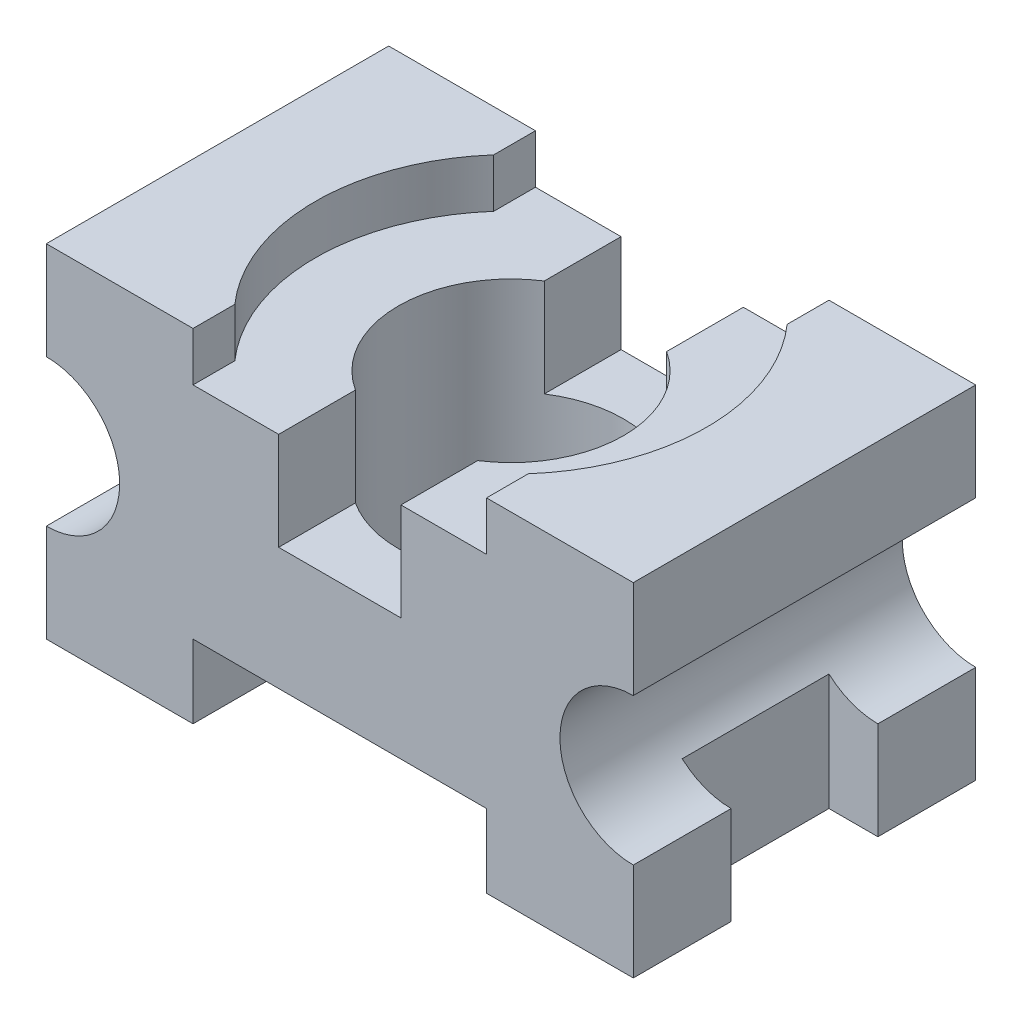
SolidWorks part; units mm, degrees
ref_plane "Front Plane" through (0, 0, 0) normal (0, 0, 1) x (1, 0, 0)
ref_plane "Top Plane" through (0, 0, 0) normal (0, 1, 0) x (1, 0, 0)
ref_plane "Right Plane" through (0, 0, 0) normal (1, 0, 0) x (0, 0, -1)
sketch "Sketch1" plane through (0, 0, 0) normal (0, 0, 1) x (1, 0, 0)
  line L0 (-60.0631, -25.7154) -> (-60.0631, -45.7154)
  line L1 (-60.0631, -45.7154) -> (-30.0631, -45.7154)
  line L2 (-0.0631, -45.7154) -> (-0.0631, 24.2846) construction
  line L3 (-60.0631, 4.2846) -> (-60.0631, 24.2846)
  line L4 (-60.0631, 24.2846) -> (-30.0631, 24.2846)
  line L5 (-30.0631, 24.2846) -> (-30.0631, 14.2846)
  line L6 (-30.0631, 14.2846) -> (-12.5631, 14.2846)
  line L7 (-12.5631, 14.2846) -> (-12.5631, -5.7154)
  line L8 (-12.5631, -5.7154) -> (12.4369, -5.7154)
  line L9 (12.4369, 14.2846) -> (12.4369, -5.7154)
  line L10 (-30.0631, -45.7154) -> (-30.0631, -30.7154)
  line L11 (-30.0631, -30.7154) -> (29.9369, -30.7154)
  line L12 (29.9369, 14.2846) -> (12.4369, 14.2846)
  line L13 (29.9369, 24.2846) -> (29.9369, 14.2846)
  line L14 (59.9369, 24.2846) -> (29.9369, 24.2846)
  line L15 (59.9369, 4.2846) -> (59.9369, 24.2846)
  line L16 (59.9369, -25.7154) -> (59.9369, -45.7154)
  line L17 (59.9369, -45.7154) -> (29.9369, -45.7154)
  line L18 (29.9369, -45.7154) -> (29.9369, -30.7154)
  arc A0 (-60.0631, -25.7154) -> (-60.0631, 4.2846) centre (-60.0631, -10.7154) ccw
  arc A1 (59.9369, -25.7154) -> (59.9369, 4.2846) centre (59.9369, -10.7154) cw
  point P16 (-0.0631, -5.7154)
  point P26 (-0.0631, -30.7154)
extrude "Boss-Extrude1" add sketch "Sketch1" along normal blind 70
sketch "Sketch2" plane through (0, 24.2846, 0) normal (0, 1, 0) x (1, 0, 0)
  circle A0 centre (-0.0631, -35) radius 40
extrude "Cut-Extrude1" cut sketch "Sketch2" against normal blind 10
sketch "Sketch3" plane through (0, 14.2846, 0) normal (0, 1, 0) x (1, 0, 0)
  circle A0 centre (-0.0631, -35) radius 23
extrude "Cut-Extrude2" cut sketch "Sketch3" against normal blind 66
sketch "Sketch4" plane through (-60.0631, 0, 0) normal (-1, 0, 0) x (0, 0, 1)
  line L0 (70, -45.7154) -> (50, -45.7154)
  line L1 (70, -45.7154) -> (0, -45.7154) construction
  line L2 (50, -45.7154) -> (20, -45.7154)
  line L3 (20, -45.7154) -> (20, -10.7154)
  line L5 (20, -10.7154) -> (50, -10.7154)
  line L6 (50, -10.7154) -> (50, -45.7154)
  line M2 (0, -45.7154) -> (70, -45.7154)
  line M4 (70, -25.7154) -> (0, -25.7154)
extrude "Cut-Extrude3" cut sketch "Sketch4" against normal blind 10 contours L6 L5 L3 M4 | L6 L3 M4 M2
ref_plane "Plane1" through (-0.0631, 0, 0) normal (-1, 0, 0) x (0, 0, 1)
mirror "Mirror1" about plane through (-0.0631, 0, 0) normal (-1, 0, 0) of "Cut-Extrude3"
